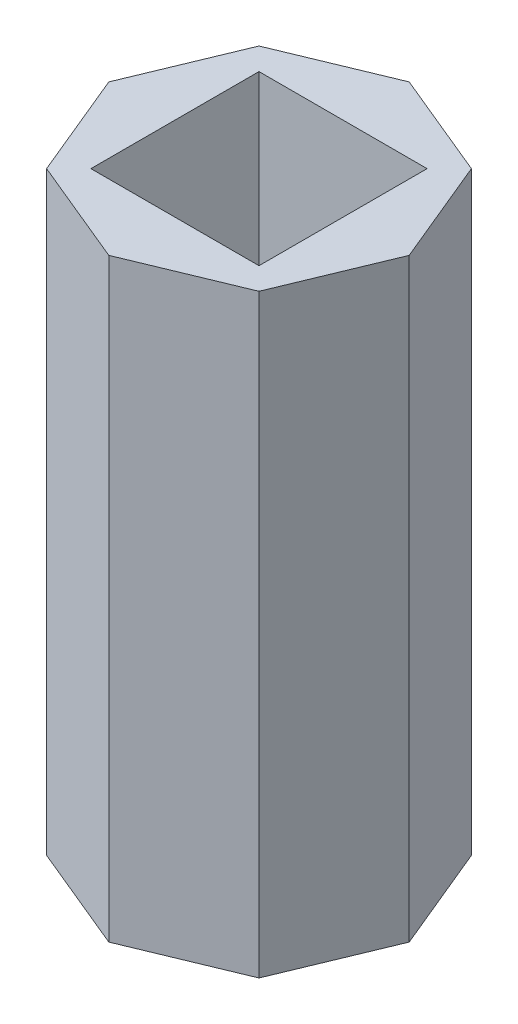
SolidWorks part; units mm, degrees
ref_plane "Front Plane" through (0, 0, 0) normal (0, 0, 1) x (1, 0, 0)
ref_plane "Top Plane" through (0, 0, 0) normal (0, 1, 0) x (1, 0, 0)
ref_plane "Right Plane" through (0, 0, 0) normal (1, 0, 0) x (0, 0, -1)
sketch "Sketch1" plane through (0, 0, 0) normal (0, 1, 0) x (1, 0, 0)
  line L0 (6.014, 0) -> (4.2526, 4.2526)
  line L1 (-3.3655, -3.3655) -> (3.3655, -3.3655)
  line L2 (-3.3655, -3.3655) -> (-3.3655, 3.3655)
  line L3 (-3.3655, 3.3655) -> (3.3655, 3.3655)
  line L4 (3.3655, -3.3655) -> (3.3655, 3.3655)
  line L5 (-3.3655, -3.3655) -> (3.3655, 3.3655) construction
  line L6 (-3.3655, 3.3655) -> (3.3655, -3.3655) construction
  line L7 (0, 6.014) -> (-4.2526, 4.2526)
  line L8 (-4.2526, 4.2526) -> (-6.014, 0)
  line L9 (-6.014, 0) -> (-4.2526, -4.2526)
  line L10 (-4.2526, -4.2526) -> (0, -6.014)
  line L11 (0, -6.014) -> (4.2526, -4.2526)
  line L12 (4.2526, -4.2526) -> (6.014, 0)
  line L13 (4.2526, 4.2526) -> (0, 6.014)
  circle A0 centre (0, 0) radius 5.5562 construction
  point P0 (0, 0)
  dimension "D2" = 11.1125
  dimension "D1" = 6.731
  dimension "D3" = 67.5
extrude "Boss-Extrude1" add sketch "Sketch1" along normal mid plane 23.8125
